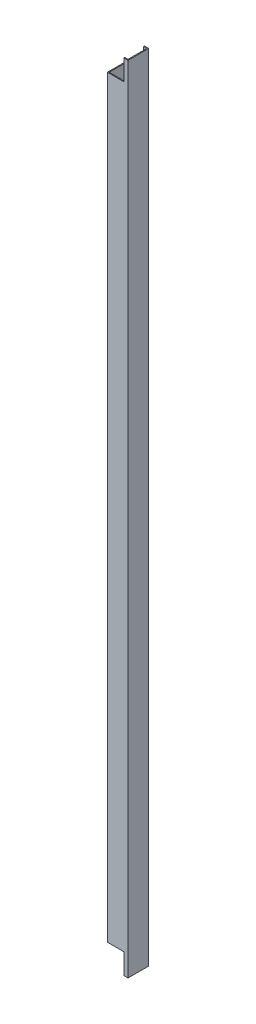
SolidWorks part; units mm, degrees
ref_plane "Front Plane" through (0, 0, 0) normal (0, 0, 1) x (1, 0, 0)
ref_plane "Top Plane" through (0, 0, 0) normal (0, 1, 0) x (1, 0, 0)
ref_plane "Right Plane" through (0, 0, 0) normal (1, 0, 0) x (0, 0, -1)
sketch "Sketch1" plane through (0, 0, 0) normal (0, 1, 0) x (1, 0, 0)
  line L0 (0, 0) -> (0, 50)
  line L1 (0, 50) -> (50, 50)
  line L2 (50, 50) -> (50, 0)
  line L3 (50, 0) -> (0, 0)
  line L4 (2.2, 47.8) -> (47.8, 47.8)
  line L5 (47.8, 47.8) -> (47.8, 2.2)
  line L6 (47.8, 2.2) -> (2.2, 2.2)
  line L7 (2.2, 2.2) -> (2.2, 47.8)
  dimension "D1" = 50
  dimension "D2" = 50
  dimension "D3" = 2.2
extrude "Boss-Extrude1" add sketch "Sketch1" along normal blind 1923
sketch "Sketch2" plane through (0, 0, 0) normal (0, 0, 1) x (1, 0, 0)
  line L0 (0, 0) -> (0, 50)
  line L1 (0, 1923) -> (0, 0) construction
  line L2 (0, 50) -> (40, 50)
  line L3 (40, 50) -> (40, 0)
  line L5 (40, 0) -> (0, 0)
  line L6 (0, 1923) -> (40, 1923)
  line L7 (0, 1923) -> (50, 1923) construction
  line L8 (40, 1923) -> (40, 1873)
  line L9 (40, 1873) -> (0, 1873)
  line L10 (0, 1873) -> (0, 1923)
  dimension "D1" = 50
  dimension "D2" = 40
  dimension "D3" = 50
  dimension "D4" = 40
extrude "Cut-Extrude2" cut sketch "Sketch2" against normal blind 50
equation "\"SquareTube_length\"=1923.0"
equation "\"D1@Boss-Extrude1\"=\"SquareTube_length\""
equation "\"SquareTube_inFront1_cutDepth50_R\"=0.5"
equation "\"D1@Sketch2\" = \"SquareTube_inFront10_cutDepth50_R\""
equation "\"SquareTube_inFront1_cutDepth50_L\"=0.5"
equation "\"D3@Sketch2\" = \"SquareTube_inFront10_cutDepth50_L\""
equation "\"CarBeamWidth\"=700.0"
equation "\"MetalSheet_3mm_length\"=5030.0"
equation "\"MetalSheet_3mm_width\"=1923.0"
equation "\"MetalSheet_3mm_FloorCut_L_length\"=1764.0"
equation "\"MetalSheet_3mm_FloorCut_L_disdance\"=1665.0"
equation "\"MetalSheet_3mm_FloorCut_R_length\"=1764.0"
equation "\"MetalSheet_3mm_FloorCut_R_disdance\"=1665.0"
equation "\"indoorHeight\"=1940.0"
equation "\"x\"=66.0"
equation "\"da\"=62.0"
equation "\"SquareTube_wheel_length\"= 750"
equation "\"channelSteel_length\"=5030.0"
equation "\"SquareTube_inFront2_cutDepth50_R\"=0.5"
equation "\"SquareTube_inFront2_cutDepth50_L\"=0.5"
equation "\"SquareTube_inFront3_cutDepth50_R\"=0.5"
equation "\"SquareTube_inFront3_cutDepth50_L\"=0.5"
equation "\"SquareTube_inFront4_cutDepth50_R\"=0.5"
equation "\"SquareTube_inFront4_cutDepth50_L\"=0.5"
equation "\"SquareTube_inFront5_cutDepth50_R\"=50"
equation "\"SquareTube_inFront5_cutDepth50_L\"=50"
equation "\"SquareTube_inFront6_cutDepth50_R\"=50"
equation "\"SquareTube_inFront6_cutDepth50_L\"=50"
equation "\"SquareTube_inFront7_cutDepth50_R\"=50"
equation "\"SquareTube_inFront7_cutDepth50_L\"=50"
equation "\"SquareTube_inFront8_cutDepth50_R\"=50"
equation "\"SquareTube_inFront8_cutDepth50_L\"=50"
equation "\"SquareTube_inFront9_cutDepth50_R\"=50"
equation "\"SquareTube_inFront9_cutDepth50_L\"=50"
equation "\"SquareTube_inFront10_cutDepth50_R\"=50"
equation "\"SquareTube_inFront10_cutDepth50_L\"=50"
equation "\"SquareTube_inBack1_cutDepth50_R\"=50"
equation "\"SquareTube_inBack1_cutDepth50_L\"=50"
equation "\"SquareTube_inBack2_cutDepth50_R\"=50"
equation "\"SquareTube_inBack2_cutDepth50_L\"=50"
equation "\"SquareTube_inBack3_cutDepth50_R\"=50"
equation "\"SquareTube_inBack3_cutDepth50_L\"=50"
equation "\"SquareTube_inBack4_cutDepth50_R\"=50"
equation "\"SquareTube_inBack4_cutDepth50_L\"=50"
equation "\"SquareTube_inBack5_cutDepth50_R\"=50"
equation "\"SquareTube_inBack5_cutDepth50_L\"=50"
equation "\"SquareTube_inBack6_cutDepth50_R\"=0.5"
equation "\"SquareTube_inBack6_cutDepth50_L\"=0.5"
